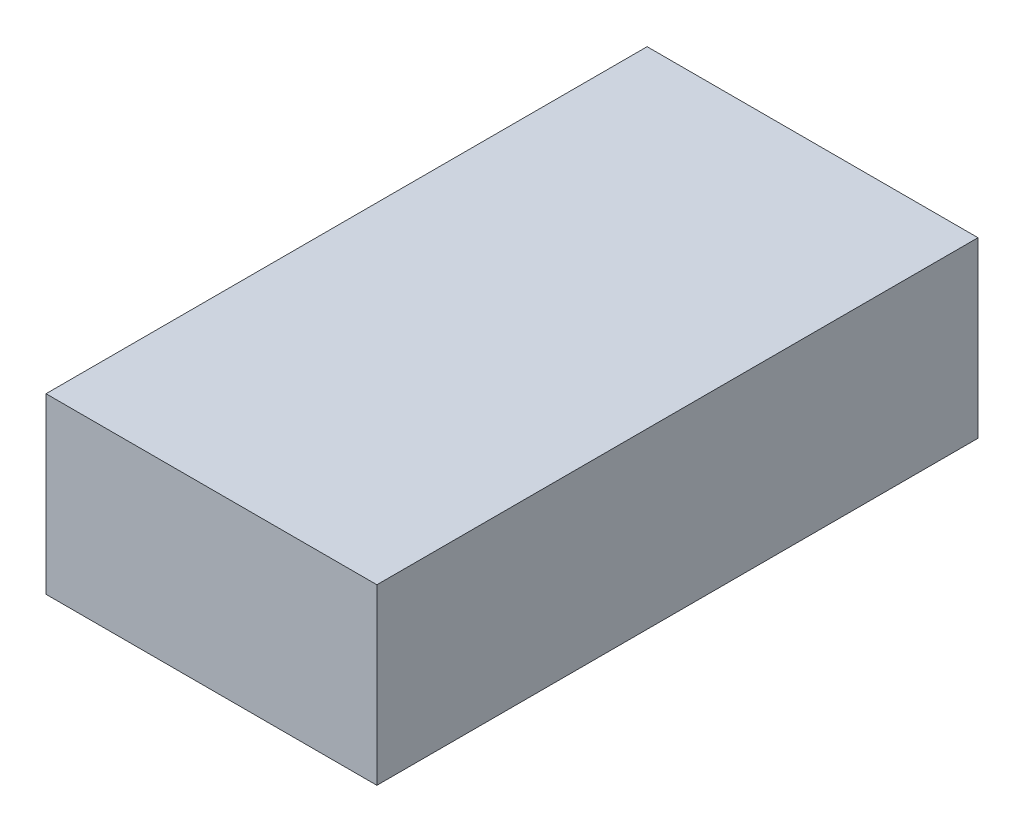
SolidWorks part; units mm, degrees
ref_plane "前视基准面" through (0, 0, 0) normal (0, 0, 1) x (1, 0, 0)
ref_plane "上视基准面" through (0, 0, 0) normal (0, 1, 0) x (1, 0, 0)
ref_plane "右视基准面" through (0, 0, 0) normal (1, 0, 0) x (0, 0, -1)
sketch "草图1" plane through (0, 0, 0) normal (0, 1, 0) x (1, 0, 0)
  line L1 (-60, -109) -> (60, -109)
  line L2 (-60, -109) -> (-60, 109)
  line L3 (-60, 109) -> (60, 109)
  line L4 (60, -109) -> (60, 109)
  line L5 (-60, -109) -> (60, 109) construction
  line L6 (-60, 109) -> (60, -109) construction
  point P0 (0, 0)
  dimension "D1" = 218
  dimension "D2" = 120
extrude "凸台-拉伸1" add sketch "草图1" along normal blind 63
